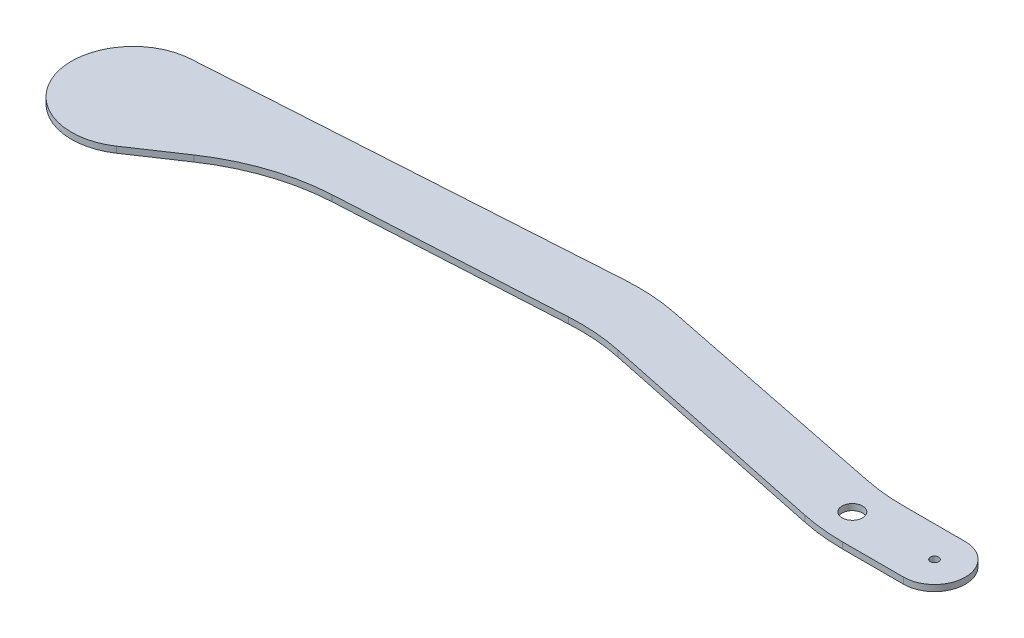
SolidWorks part; units mm, degrees
ref_plane "Front Plane" through (0, 0, 0) normal (0, 0, 1) x (1, 0, 0)
ref_plane "Top Plane" through (0, 0, 0) normal (0, 1, 0) x (1, 0, 0)
ref_plane "Right Plane" through (0, 0, 0) normal (1, 0, 0) x (0, 0, -1)
sketch "Sketch1" plane through (0, 0, 0) normal (0, 1, 0) x (1, 0, 0)
  line L0 (0, 0) -> (-350, 0) construction
  line L1 (0, 0) -> (40, 0) construction
  line L2 (0, 15) -> (40, 15)
  line L3 (0, -15) -> (40, -15)
  line L4 (-351.8754, 29.9413) -> (-333.2857, -24.9125) construction
  line L5 (-139.7849, 43.2259) -> (-4217.6379, -212.1962)
  line L6 (0, 15) -> (-4004.6012, 823.6244)
  line L7 (0, 15) -> (-5.9197, -13.7825) construction
  line L8 (-4217.6379, -212.1962) -> (-138.0533, 13.889)
  line L9 (-4004.6012, 823.6244) -> (-5.9197, -13.7825)
  line L10 (-333.2857, -24.9125) -> (-287.8235, 5.5889)
  line L11 (-5.9197, -13.7825) -> (0, -15)
  circle A0 centre (0, 0) radius 5
  circle A1 centre (-350, 0) radius 30
  circle A2 centre (40, 0) radius 2
  circle A3 centre (0, 0) radius 15
  circle A4 centre (40, 0) radius 15
  dimension "D1" = 10
  dimension "D4" = 4
  dimension "D5" = 60
  dimension "D6" = 30
  dimension "D7" = 165
  dimension "D2" = 350
  dimension "D3" = 40
  dimension "D8" = 165
  dimension "D9" = 135
  dimension "D10" = 150
extrude "Boss-Extrude1" add sketch "Sketch1" along normal blind 3 contours L8 A1 | A1 L8 | A1 L8 L9 L5 | A1 L10 L8 | A3 L6 L5 L9 | A3 A0 | A4 L2 A3 L3 | A4 A2
fillet "Fillet1" radius 100 5 edges at (0, 1.5, -15) (-139.7849, 1.5, -43.2259) (-138.0533, 1.5, -13.889) (-287.8235, 1.5, -5.5889) (0, 1.5, 15)
